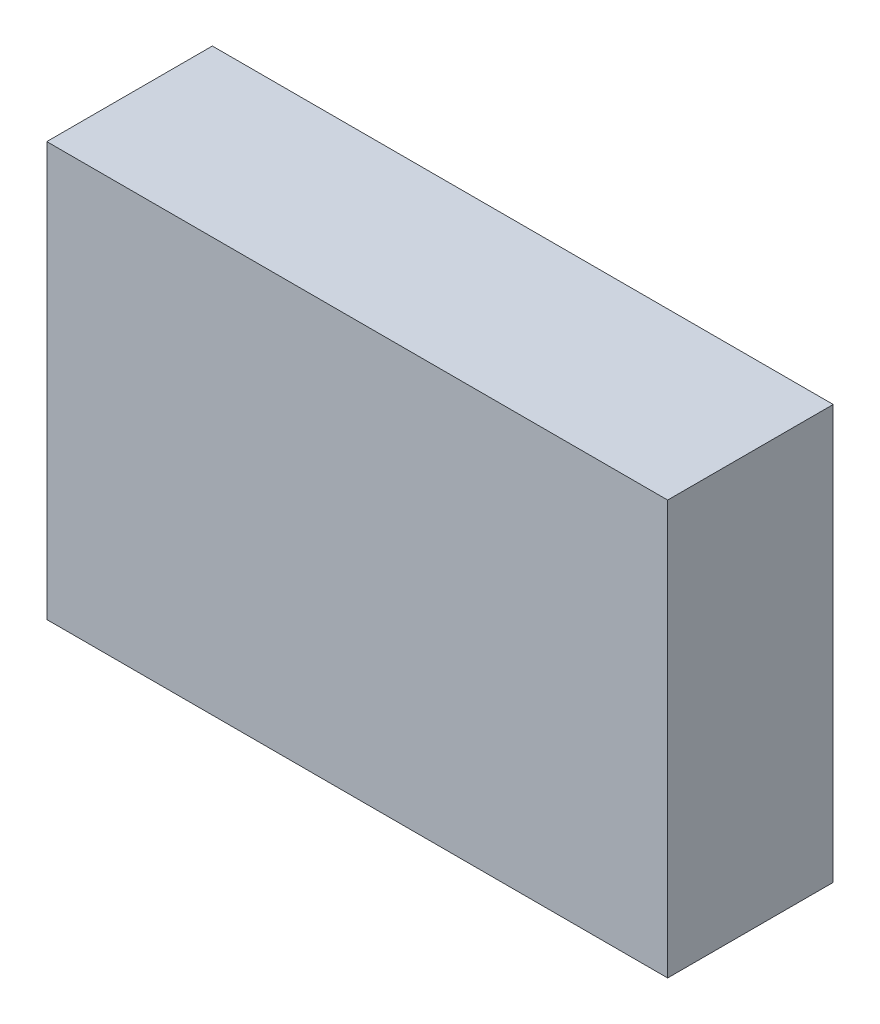
SolidWorks part; units mm, degrees
ref_plane "前视基准面" through (0, 0, 0) normal (0, 0, 1) x (1, 0, 0)
ref_plane "上视基准面" through (0, 0, 0) normal (0, 1, 0) x (1, 0, 0)
ref_plane "右视基准面" through (0, 0, 0) normal (1, 0, 0) x (0, 0, -1)
other "Configuration Table"
sketch "草图1" plane through (0, 0, 0) normal (0, 0, 1) x (1, 0, 0)
  line L1 (-37.5, -25) -> (37.5, -25)
  line L2 (-37.5, -25) -> (-37.5, 25)
  line L3 (-37.5, 25) -> (37.5, 25)
  line L4 (37.5, -25) -> (37.5, 25)
  line L5 (-37.5, -25) -> (37.5, 25) construction
  line L6 (-37.5, 25) -> (37.5, -25) construction
  point P0 (0, 0)
  dimension "D1" = 50
  dimension "D2" = 75
extrude "凸台-拉伸1" add sketch "草图1" along normal blind 20
